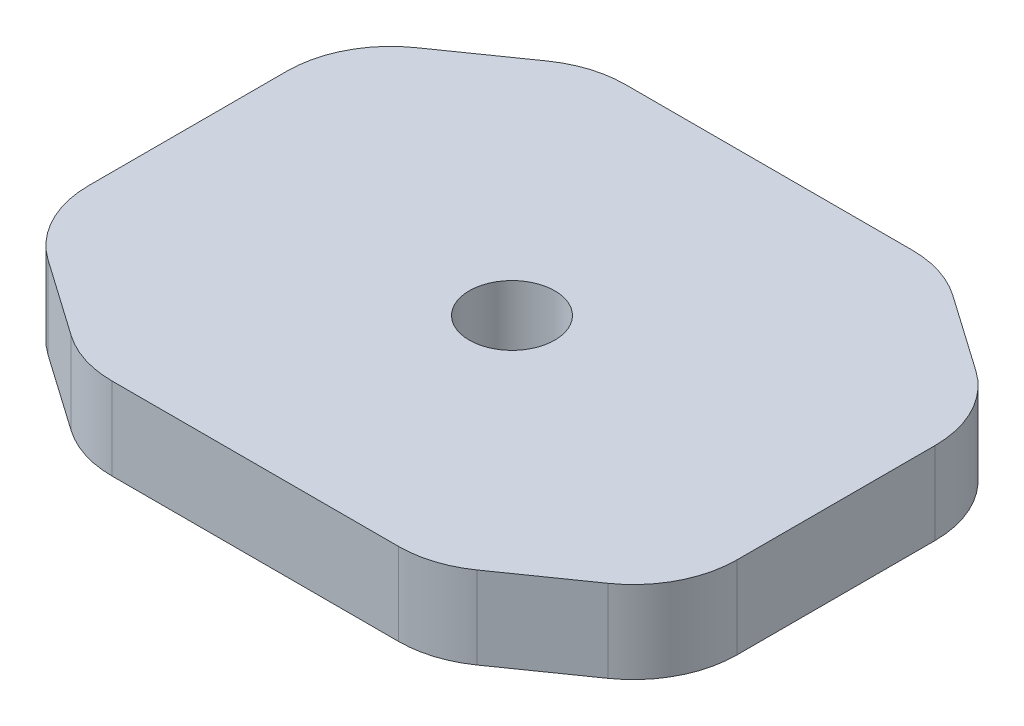
SolidWorks part; units mm, degrees
ref_plane "Front Plane" through (0, 0, 0) normal (0, 0, 1) x (1, 0, 0)
ref_plane "Top Plane" through (0, 0, 0) normal (0, 1, 0) x (1, 0, 0)
ref_plane "Right Plane" through (0, 0, 0) normal (1, 0, 0) x (0, 0, -1)
sketch "Sketch2" plane through (0, 0, 0) normal (0, 1, 0) x (1, 0, 0)
  line L1 (-12.5, 9.9) -> (12.5, 9.9)
  line L2 (-12.5, 9.9) -> (-12.5, -9.9)
  line L3 (-12.5, -9.9) -> (12.5, -9.9)
  line L4 (12.5, 9.9) -> (12.5, -9.9)
  line L5 (-12.5, 9.9) -> (12.5, -9.9) construction
  line L6 (-12.5, -9.9) -> (12.5, 9.9) construction
  point P0 (0, 0)
  dimension "D1" = 19.8
  dimension "D2" = 25
extrude "Boss-Extrude2" add sketch "Sketch2" along normal blind 3.175
sketch "Sketch3" plane through (0, 3.175, 0) normal (0, 1, 0) x (1, 0, 0)
  circle A0 centre (0, 0) radius 1.65
  dimension "D1" = 3.3
extrude "Cut-Extrude1" cut sketch "Sketch3" against normal up to surface (3.175 mm away) up to face at (0, 0, 0)
chamfer "Chamfer1" distance 4 angle 55 4 edges at (12.5, 1.5875, 9.9) (-12.5, 1.5875, 9.9) (-12.5, 1.5875, -9.9) (12.5, 1.5875, -9.9)
fillet "Fillet2" radius 4 8 edges at (6.7874, 1.5875, -9.9) (-6.7874, 1.5875, -9.9) (-12.5, 1.5875, -5.9) (-12.5, 1.5875, 5.9) (-6.7874, 1.5875, 9.9) (6.7874, 1.5875, 9.9) (12.5, 1.5875, 5.9) (12.5, 1.5875, -5.9)
chamfer "3D-print" [suppressed] distance 0.4 angle 45
